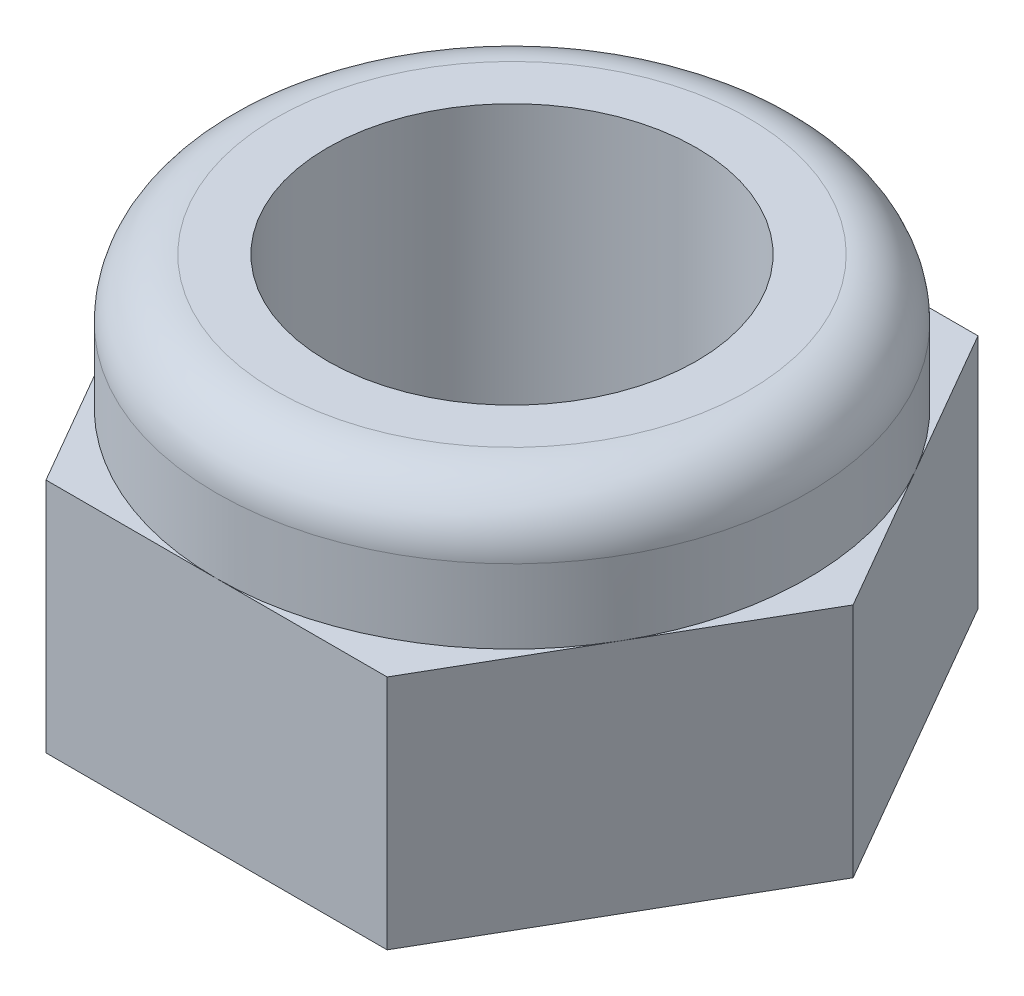
SolidWorks part; units mm, degrees
ref_plane "Front Plane" through (0, 0, 0) normal (0, 0, 1) x (1, 0, 0)
ref_plane "Top Plane" through (0, 0, 0) normal (0, 1, 0) x (1, 0, 0)
ref_plane "Right Plane" through (0, 0, 0) normal (1, 0, 0) x (0, 0, -1)
sketch "Sketch1" plane through (0, 0, 0) normal (0, 1, 0) x (1, 0, 0)
  line L1 (4.6188, 0) -> (2.3094, 4)
  line L2 (2.3094, 4) -> (-2.3094, 4)
  line L3 (-2.3094, 4) -> (-4.6188, 0)
  line L4 (-4.6188, 0) -> (-2.3094, -4)
  line L5 (-2.3094, -4) -> (2.3094, -4)
  line L6 (2.3094, -4) -> (4.6188, 0)
  circle A0 centre (0, 0) radius 4 construction
  dimension "D1" = 8
extrude "Boss-Extrude1" add sketch "Sketch1" along normal blind 3.2
sketch "Sketch2" plane through (0, 3.2, 0) normal (0, 1, 0) x (1, 0, 0)
  circle A0 centre (0, 0) radius 4 construction
  circle A1 centre (0, 0) radius 4
extrude "Boss-Extrude2" add sketch "Sketch2" along normal offset from surface (1.8 mm away) 5 up to face at (0, 0, 0)
sketch "Sketch3" plane through (0, 5, 0) normal (0, 1, 0) x (1, 0, 0)
  circle A0 centre (0, 0) radius 2.5
  dimension "D1" = 5
extrude "Cut-Extrude1" cut sketch "Sketch3" against normal through all
fillet "Fillet1" radius 0.8 1 edges at (0, 5, 4)
